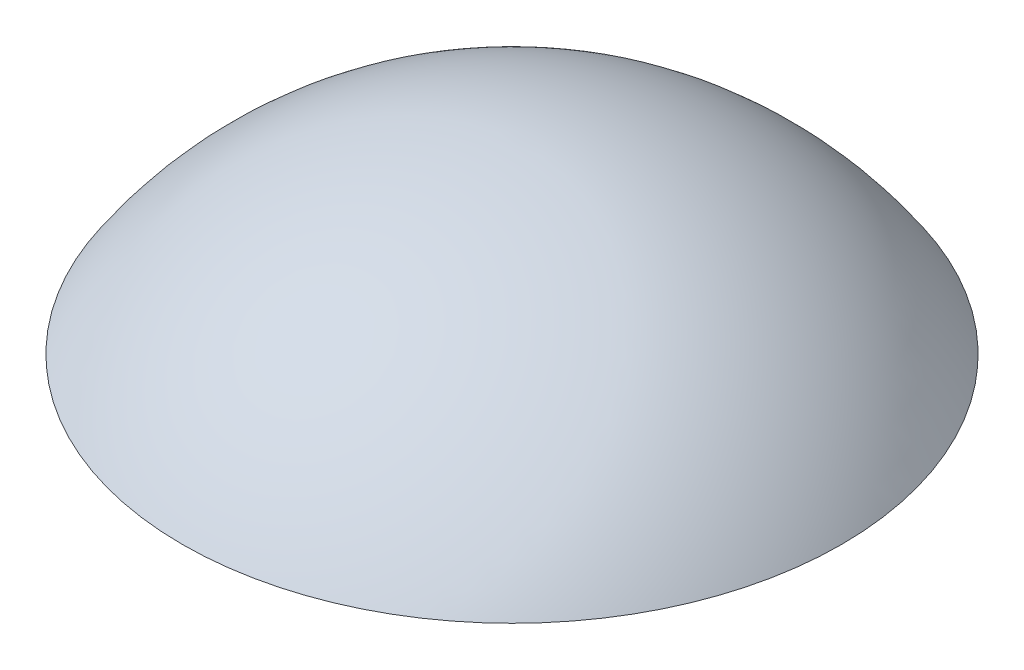
SolidWorks part; units mm, degrees
ref_plane "Front" through (0, 0, 0) normal (0, 0, 1) x (1, 0, 0)
ref_plane "Top" through (0, 0, 0) normal (0, 1, 0) x (1, 0, 0)
ref_plane "Right" through (0, 0, 0) normal (1, 0, 0) x (0, 0, -1)
sketch "Sketch6" plane through (0, 0, 0) normal (0, 0, 1) x (1, 0, 0)
  line L0 (0, 60.2442) -> (0, 7.28) construction
  line L2 (0, -16.2) -> (0, -60.6715) construction
  line L7 (0, 7.8) -> (0, 7.28)
  line L9 (0, -16.2) -> (0, -16.52)
  arc A0 (6.5209, 4.28) -> (0, 7.8) centre (0, 0) ccw
  arc A1 (5.5482, 4.3361) -> (0, 7.28) centre (0, 0.58) ccw
  spline S0 degree 3 poles (5.5482, 4.3361) (5.403, 5.0449) (6.0513, 4.9263) (6.5209, 4.28) knots 0 0 0 0 1 1 1 1
  dimension "D9" = 0.52
  dimension "D12" = 7.8
  dimension "D16" = 6.7
revolve "Revolve1" add sketch "Sketch6" angle 360 about L0
